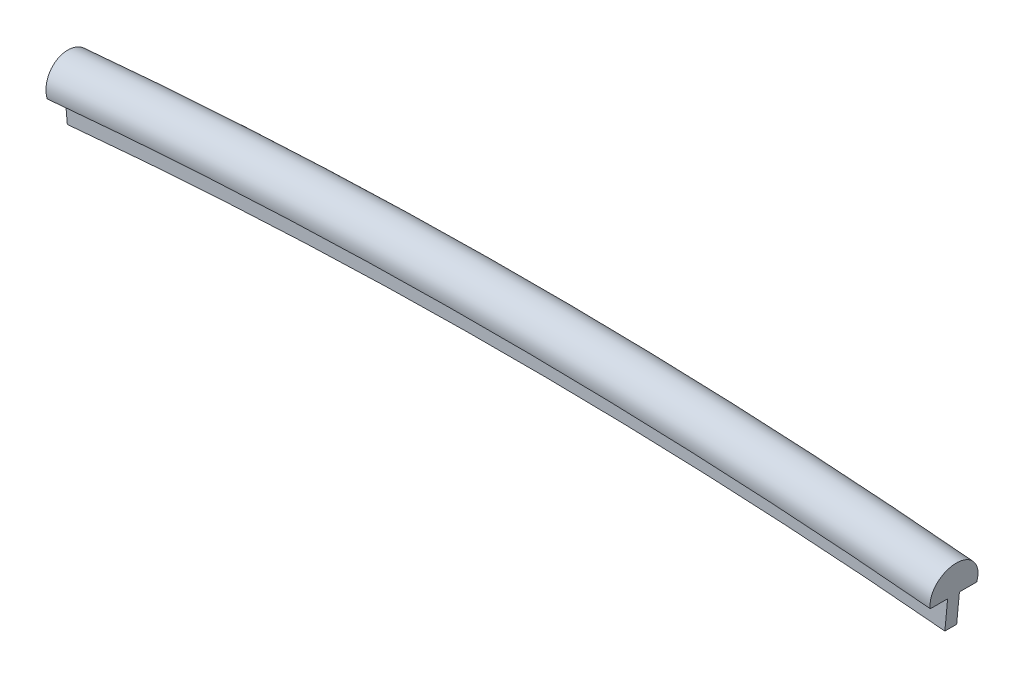
SolidWorks part; units mm, degrees
ref_plane "Front Plane" through (0, 0, 0) normal (0, 0, 1) x (1, 0, 0)
ref_plane "Top Plane" through (0, 0, 0) normal (0, 1, 0) x (1, 0, 0)
ref_plane "Right Plane" through (0, 0, 0) normal (1, 0, 0) x (0, 0, -1)
sketch "Sketch2" plane through (0, 0, 0) normal (1, 0, 0) x (0, 0, -1)
  line L0 (0, 241.3) -> (0, 0) construction
  line L2 (0, 241.3) -> (0, 239.8) construction
  line L3 (0, 239.8) -> (0.3, 239.8)
  line L4 (0, 239.8) -> (-0.3, 239.8)
  line L5 (-0.3, 239.8) -> (-0.3, 241.3)
  line L6 (0.3, 239.8) -> (0.3, 241.3)
  line L7 (0, 241.3) -> (0, 242.8) construction
  line L8 (-1.18, 241.3) -> (-0.3, 241.3)
  line L9 (0.3, 241.3) -> (1.18, 241.3)
  arc A0 (-1.18, 241.3) -> (1.18, 241.3) centre (0, 241.586) cw
  point P14 (0, 241.3)
ref_axis "Axis2" through (0, 0, 70.5976) along (0, 0, -1)
revolve "Revolve1" add sketch "Sketch2" angle 5.339 about axis through (0, 0, 70.5976) along (0, 0, -1)
